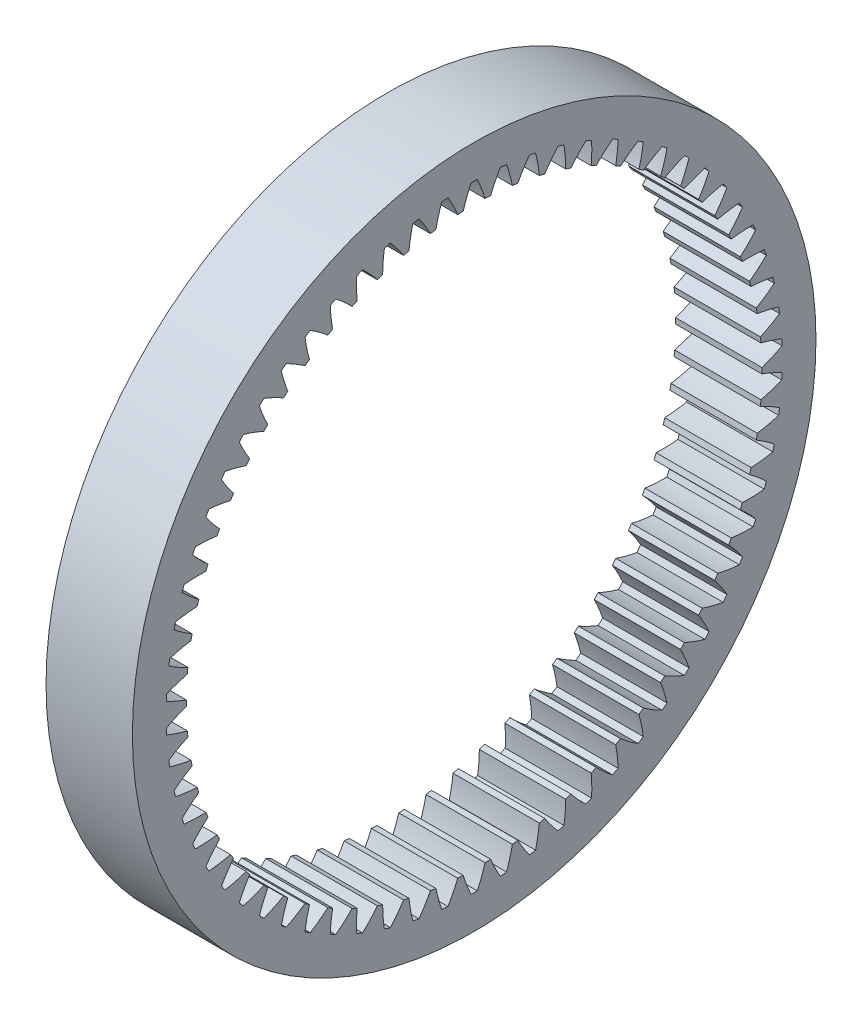
SolidWorks part; units mm, degrees
ref_plane "Plane1" through (0, 0, 0) normal (0, 0, 1) x (1, 0, 0)
ref_plane "Plane2" through (0, 0, 0) normal (0, 1, 0) x (1, 0, 0)
ref_plane "Plane3" through (0, 0, 0) normal (1, 0, 0) x (0, 0, -1)
other "Configuration Table"
sketch "HoldingSke" plane through (0, 0, 0) normal (0, 1, 0) x (1, 0, 0)
  line L0 (0, 0) -> (0.3254, -0.7308)
  line L1 (-15, 0) -> (100, 0) construction
  line L2 (0, 0) -> (-2.1039, 2.3779)
  line L3 (0, 0) -> (-11.863, 4.5341)
  line L4 (0, 0) -> (3.5126, 7.8894)
  line L5 (0, 0) -> (-23.7986, -8.8762)
  line L6 (0, 0) -> (-10.5278, -7.1032)
  line L7 (-2.1039, 2.3779) -> (3.3635, 27.1825)
  line L8 (-76.2, 3.6279) -> (-54.61, 3.6279)
  line L9 (-71.009, 38.7566) -> (-53.1078, 45.2721)
  line L10 (-76.2, 71.12) -> (104.1128, 71.12)
  line L11 (0, 0) -> (-12, 0)
  line L12 (-76.2, 101.6) -> (-76.155, 101.6)
  line L13 (24.9733, 27.94) -> (52.9518, 28.4284)
  line L14 (24.9733, 27.94) -> (24.9743, 27.94)
  line L15 (24.9733, 27.94) -> (100.4006, 29.5858)
  circle A0 centre (0, 0) radius 47.5
  circle A1 centre (0, 0) radius 12.7
  circle A2 centre (0, 0) radius 12.7
  dimension "MHD" = 25.4
  dimension "Hub_dia" = 25.4
  dimension "Diameter" = 95
  dimension "Num_teeth" = 66
  dimension "Pitch" = 0.8
  dimension "Overall_len" = 25.4
  dimension "Show_teeth" = 66
  dimension "Thickness" = 12.7
  dimension "OAL" = 25.4001
  dimension "T_dim" = 21.59
  dimension "Ap" = 20
  dimension "H" = 19.05
  dimension "Pitch_radius" = 180.3128
  dimension "Width" = 12
  dimension "Backlash" = 0.045
  dimension "Addendum_fac" = 1
  dimension "Dedendum_fac" = 1.25
  dimension "Clearance_fac" = 0.25
  dimension "Dedendum_add" = 0.001
  dimension "Module" = 1.25
sketch "BasProSke" plane through (0, 0, 0) normal (0, 1, 0) x (1, 0, 0)
  line L0 (-10, 0) -> (60, 0) construction
  line L1 (0, 40) -> (0, 47.5)
  line L2 (0, 40) -> (12, 40)
  line L3 (12, 40) -> (12, 47.5)
  line L4 (12, 47.5) -> (0, 47.5)
  dimension "Diameter" = 95
  dimension "Thickness" = 12
  dimension "Inside_diameter" = 80
revolve "Base-Revolve" add sketch "BasProSke" angle 360 about L0
sketch "TooCutSke" plane through (0, 0, 0) normal (1, 0, 0) x (0, 0, -1)
  line L3 (1.0942, 41.2355) -> (1.0942, 53.6633) construction
  line L4 (0, 0) -> (0, 59.563) construction
  line L5 (0, 0) -> (-3.2512, 68.2501) construction
  line L6 (-18.2412, 34.0567) -> (36.14, 36.6472) construction
  circle A0 centre (0, 0) radius 41.25 construction
  circle A1 centre (0, 0) radius 42.8135 construction
  circle A2 centre (0, 0) radius 34.8861 construction
  circle A3 centre (0, 0) radius 39.9746 construction
  arc A4 (1.5253, 39.9455) -> (0.4336, 42.8113) centre (-18.2412, 34.0567) ccw
  arc A5 (1.5253, 39.9455) -> (-1.5253, 39.9455) centre (0, 0) ccw
  arc A6 (0.4336, 42.8113) -> (-0.4336, 42.8113) centre (0, 0) ccw
  arc A7 (-0.4336, 42.8113) -> (-1.5253, 39.9455) centre (18.2412, 34.0567) ccw
  dimension "Pitch_dia" = 82.5
  dimension "Base_dia" = 69.7722
  dimension "Root_dia" = 85.627
  dimension "Overcut_dia" = 79.9492
  dimension "Flank_rad" = 20.625
  dimension "Half_ang" = 2.727
  dimension "Half_CT" = 1.0942
extrude "ToothCut" cut sketch "TooCutSke" along normal through all
fillet "Breaks" [suppressed] radius 0.125
fillet "RootFillets" [suppressed] radius 0.3135
pattern_circular "TeethCuts" count 66 every 5.455 about axis through (-10, 0, 0) along (1, 0, 0) of "RootFillets", "Breaks", "ToothCut"
equation "' \"Module@HoldingSke\" = 6.35"
equation "' \"Num_teeth@HoldingSke\" = 24"
equation "' \"Ap@HoldingSke\" =  14.5"
equation "' \"Ap@HoldingSke\" = 14.5"
equation "' \"Width@HoldingSke\" = 12"
equation "' \"Diameter@HoldingSke\" = 8 * 25.4"
equation "' \"Show_teeth@HoldingSke\" = 100"
equation "' \"Backlash@HoldingSke\" = 0.009 * 25.4"
equation "' \"Addendum_fac@HoldingSke\" = 1.0"
equation "' \"Dedendum_fac@HoldingSke\" = 1.25"
equation "' \"Dedendum_add@HoldingSke\" = 0.00005 * 25.4"
equation "' \"Clearance_fac@HoldingSke\" = 0.25"
equation "\"Pitch@HoldingSke\" = 1 / \"Module@HoldingSke\" "
equation "\"Overcut_dia@TooCutSke\" = (\"Num_teeth@HoldingSke\" - 2 * \"Addendum_fac@HoldingSke\") / \"Pitch@HoldingSke\" - 0.002 * 25.4"
equation "\"Pitch_dia@TooCutSke\" = \"Num_teeth@HoldingSke\" / \"Pitch@HoldingSke\""
equation "\"Base_dia@TooCutSke\" = \"Num_teeth@HoldingSke\" / \"Pitch@HoldingSke\" * cos((\"Ap@HoldingSke\"  * 3.14159265 / 180)) * 0.90"
equation "\"Root_dia@TooCutSke\" = \"Num_teeth@HoldingSke\"  / \"Pitch@HoldingSke\" + 2 *  \"Dedendum_fac@HoldingSke\"/ \"Pitch@HoldingSke\" + \"Dedendum_add@HoldingSke\" * 2"
equation "\"Half_ang@TooCutSke\" = 180 / \"Num_teeth@HoldingSke\""
equation "\"Half_CT@TooCutSke\" = \"Num_teeth@HoldingSke\" / \"Pitch@HoldingSke\" * sin((3.14159265 / 2 / \"Num_teeth@HoldingSke\")) / 2 + 10 * \"Backlash@HoldingSke\" / 4"
equation "\"Flank_rad@TooCutSke\" = \"Num_teeth@HoldingSke\" / \"Pitch@HoldingSke\" / 4"
equation "\"Radius@RootFillets\"= \"Clearance_fac@HoldingSke\" / \"Pitch@HoldingSke\" + \"Dedendum_add@HoldingSke\""
equation "\"Break_rad@Breaks\" = 0.02 / \"Pitch@HoldingSke\" * 5"
equation "\"Num_teeth@TeethCuts\" = int( \"Show_teeth@HoldingSke\" ) + 1"
equation "\"Num_teeth@TeethCuts\" = ((sgn( \"Num_teeth@TeethCuts\" - \"Num_teeth@HoldingSke\" )-1)*( \"Num_teeth@TeethCuts\" - \"Num_teeth@HoldingSke\" ))/-2+ \"Num_teeth@HoldingSke\""
equation "\"Num_teeth@TeethCuts\" = ((sgn( \"Num_teeth@TeethCuts\" - 2.0)+1)*( \"Num_teeth@TeethCuts\" - 2.0))/2 +2.0"
equation "\"Angle@TeethCuts\" = 360.0 / \"Num_teeth@HoldingSke\""
equation "\"Diameter@BasProSke\" = \"Num_teeth@HoldingSke\"  / \"Pitch@HoldingSke\" + 2 *  \"Dedendum_fac@HoldingSke\"/ \"Pitch@HoldingSke\" + \"Dedendum_add@HoldingSke\" * 2 + 0.002 * 25.4"
equation "\"Diameter@BasProSke\" = ((sgn( \"Diameter@BasProSke\"  - \"Diameter@HoldingSke\" )+1)*( \"Diameter@BasProSke\"  - \"Diameter@HoldingSke\" ))/2 + \"Diameter@HoldingSke\""
equation "\"Inside_diameter@BasProSke\" =  (\"Num_teeth@HoldingSke\" - 2 * \"Addendum_fac@HoldingSke\") / \"Pitch@HoldingSke\" "
equation "\"Thickness@BasProSke\"  = \"Width@HoldingSke\""
